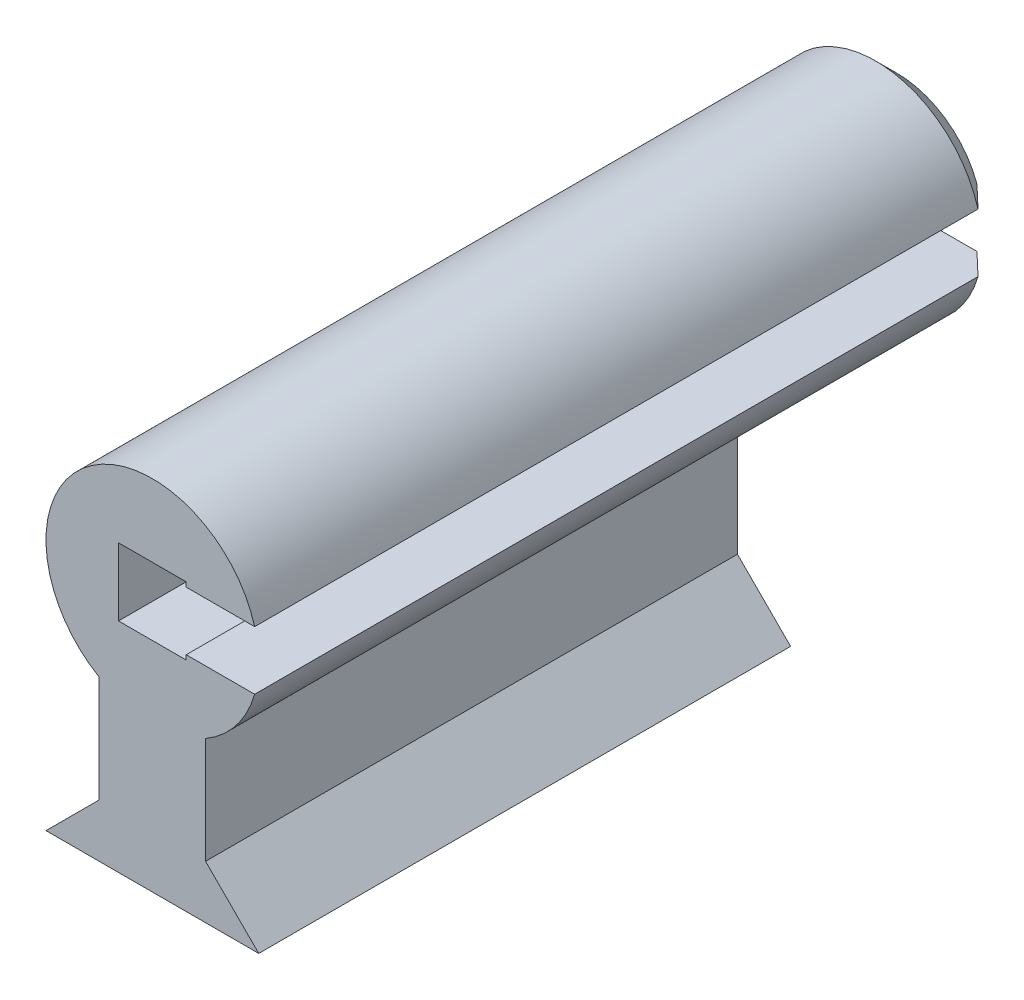
SolidWorks part; units mm, degrees
ref_plane "Front Plane" through (0, 0, 0) normal (0, 0, 1) x (1, 0, 0)
ref_plane "Top Plane" through (0, 0, 0) normal (0, 1, 0) x (1, 0, 0)
ref_plane "Right Plane" through (0, 0, 0) normal (1, 0, 0) x (0, 0, -1)
sketch "Esquisse1" plane through (0, 0, 0) normal (0, 0, 1) x (1, 0, 0)
  line L0 (3.182, 2.75) -> (3.182, 3.182)
  line L2 (9.6144, -2.75) -> (3.182, -2.75)
  line L4 (9.6144, 2.75) -> (3.182, 2.75)
  line L5 (-3.182, -3.182) -> (3.182, -3.182)
  line L6 (-3.182, -3.182) -> (-3.182, 3.182)
  line L7 (-3.182, 3.182) -> (3.182, 3.182)
  line L8 (3.182, -3.182) -> (3.182, -2.75)
  line L9 (-3.182, -3.182) -> (3.182, 3.182) construction
  line L10 (-3.182, 3.182) -> (3.182, -3.182) construction
  arc A1 (9.6144, 2.75) -> (9.6144, -2.75) centre (0, 0) ccw
  dimension "D1" = 9
  dimension "D2" = 10
  dimension "D3" = 5.5
extrude "Boss.-Extru.1" add sketch "Esquisse1" along normal blind 60 and the other way blind 10
sketch "Esquisse3" plane through (0, 0, 60) normal (0, 0, 1) x (1, 0, 0)
  line L2 (5, -8.6603) -> (5, -18.6603)
  line L4 (-5, -8.6603) -> (-5, -18.6603)
  line L7 (10, -23.6603) -> (-10, -23.6603)
  line L9 (5, -18.6603) -> (10, -23.6603)
  line L10 (-5, -18.6603) -> (-10, -23.6603)
  circle A0 centre (0, 0) radius 10 construction
  arc A1 (5, -8.6603) -> (-5, -8.6603) centre (0, 0) cw
  point P7 (0, -23.6603)
  dimension "D1" = 10
  dimension "D2" = 10
  dimension "D3" = 5
  dimension "D4" = 45
extrude "Boss.-Extru.2" add sketch "Esquisse3" against normal blind 50
chamfer "Chanfrein1" distance 2 angle 45 1 edges at (-10, 0, -10)
